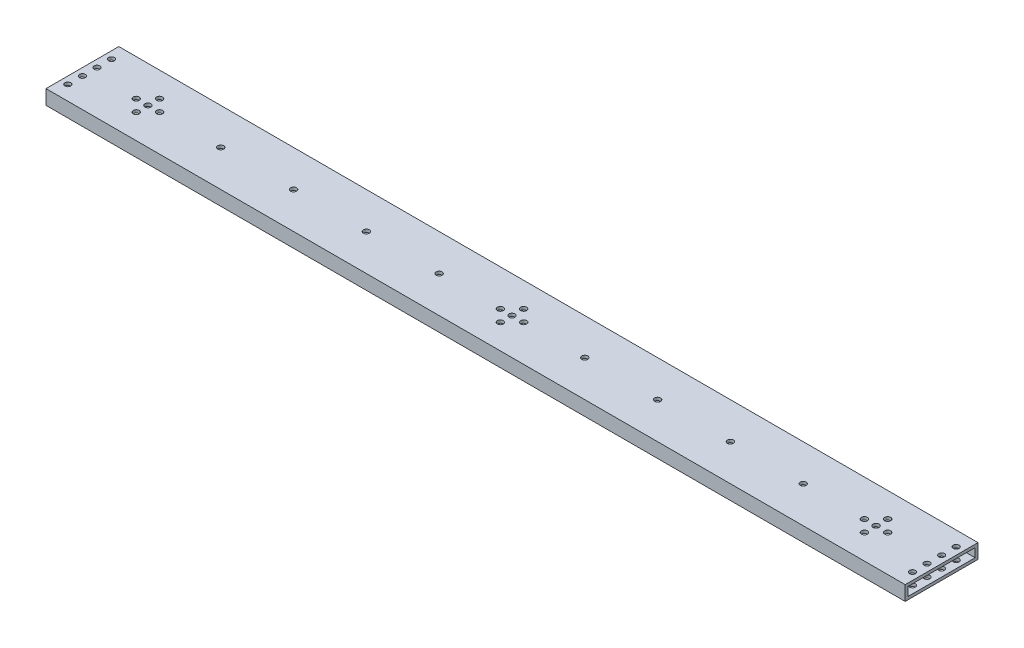
SolidWorks part; units mm, degrees
material "3.0205 (EN-AW 1200)"
ref_plane "前视基准面" through (0, 0, 0) normal (0, 0, 1) x (1, 0, 0)
ref_plane "上视基准面" through (0, 0, 0) normal (0, 1, 0) x (1, 0, 0)
ref_plane "右视基准面" through (0, 0, 0) normal (1, 0, 0) x (0, 0, -1)
sketch "草图1" plane through (0, 0, 0) normal (0, 1, 0) x (1, 0, 0)
  line L1 (-350, 25) -> (350, 25)
  line L2 (-350, 25) -> (-350, -25)
  line L3 (-350, -25) -> (350, -25)
  line L4 (350, 25) -> (350, -25)
  line L5 (-350, 25) -> (350, -25) construction
  line L6 (-350, -25) -> (350, 25) construction
  point P0 (0, 0)
  dimension "D1" = 700
  dimension "D2" = 50
extrude "凸台-拉伸1" add sketch "草图1" along normal blind 10
sketch "草图2" plane through (0, 10, 0) normal (0, 1, 0) x (1, 0, 0)
  line L0 (-350, 0) -> (541.3083, 0) construction
  line L1 (-350, 25) -> (-350, -25) construction
  circle A0 centre (-350, 0) radius 2.05 construction
  circle A15 centre (-300, 0) radius 2.05
  circle A16 centre (-250, 0) radius 2.05
  circle A17 centre (-200, 0) radius 2.05
  circle A18 centre (-150, 0) radius 2.05
  circle A19 centre (-100, 0) radius 2.05
  circle A20 centre (-50, 0) radius 2.05
  circle A21 centre (0, 0) radius 2.05
  circle A22 centre (50, 0) radius 2.05
  circle A23 centre (100, 0) radius 2.05
  circle A24 centre (150, 0) radius 2.05
  circle A25 centre (200, 0) radius 2.05
  circle A26 centre (250, 0) radius 2.05
  circle A28 centre (300, 0) radius 2.05 construction
  circle A29 centre (300, 0) radius 2.05
  circle A30 centre (350, 0) radius 2.05 construction
  circle A33 centre (400, 0) radius 2.05 [skipped]
  circle A34 centre (450, 0) radius 2.05 [skipped]
  dimension "D1" = 4.1
  dimension "D2" = 14
  dimension "D3" = 5
extrude "切除-拉伸2" cut sketch "草图2" against normal through all
sketch "草图3" plane through (0, 10, 0) normal (0, 1, 0) x (1, 0, 0)
  line L0 (-250, 0) -> (-227.6132, 0) construction
  circle A0 centre (-242, 0) radius 2.05
  circle A1 centre (-258, 0) radius 2.05
  circle A2 centre (-8, 0) radius 2.05
  circle A3 centre (8, 0) radius 2.05
  circle A4 centre (242, 0) radius 2.05
  circle A5 centre (258, 0) radius 2.05
  circle A6 centre (-250, 0) radius 2.05 construction
  circle A7 centre (-250, 8) radius 2.05
  circle A8 centre (-250, -8) radius 2.05
  circle A9 centre (0, 8) radius 2.05
  circle A10 centre (0, -8) radius 2.05
  circle A11 centre (250, 8) radius 2.05
  circle A12 centre (250, -8) radius 2.05
  dimension "D1" = 4.1
  dimension "D2" = 4.1
  dimension "D4" = 8
  dimension "D5" = 8
  dimension "D6" = 4.1
  dimension "D7" = 4.1
  dimension "D8" = 8
  dimension "D9" = 8
  dimension "D3" = 3
extrude "切除-拉伸3" cut sketch "草图3" against normal through all
sketch "草图4" plane through (-350, 0, 0) normal (-1, 0, 0) x (0, 0, 1)
  line L0 (0, 0) -> (0, 16.7886) construction
  line L1 (-25, 0) -> (25, 0) construction
  line L2 (25, 5) -> (-32.5838, 5) construction
  line L3 (25, 10) -> (25, 0) construction
  line L4 (-25, 10) -> (25, 10) construction
  line L5 (-23, 8) -> (23, 8)
  line L6 (-23, 8) -> (-23, 2)
  line L7 (-23, 2) -> (23, 2)
  line L8 (23, 8) -> (23, 2)
  line L9 (-23, 8) -> (23, 2) construction
  line L10 (-23, 2) -> (23, 8) construction
  point P8 (0, 5)
  dimension "D1" = 46
  dimension "D2" = 2
extrude "切除-拉伸4" cut sketch "草图4" against normal through all
sketch "草图6" plane through (350, 0, 0) normal (1, 0, 0) x (0, 0, -1)
  line L4 (-25, 0) -> (25, 0)
  line L5 (25, 0) -> (25, 10)
  line L6 (25, 10) -> (-25, 10)
  line L7 (-25, 10) -> (-25, 0)
  line L8 (-25, 0) -> (25, 0)
  line L9 (25, 0) -> (25, 10)
  line L10 (25, 10) -> (-25, 10)
  line L11 (-25, 10) -> (-25, 0)
  dimension "D1" = 0
extrude "切除-拉伸6" cut sketch "草图6" against normal blind 5
mirror "镜向1" about plane through (0, 0, 0) normal (1, 0, 0) of "切除-拉伸6"
sketch "草图7" plane through (0, 10, 0) normal (0, 1, 0) x (1, 0, 0)
  line L0 (340, 32.168) -> (340, -42.8527) construction
  line L1 (345, 25) -> (345, -25) construction
  line L2 (345, 25) -> (-345, 25) construction
  circle A0 centre (340, 15) radius 2
  circle A1 centre (340, 5) radius 2
  circle A2 centre (340, -5) radius 2
  circle A3 centre (340, -15) radius 2
  circle A4 centre (290, 5) radius 2
  circle A5 centre (290, 15) radius 2
  circle A6 centre (290, -5) radius 2
  circle A7 centre (290, -15) radius 2
  dimension "D2" = 4
  dimension "D3" = 10
  dimension "D5" = 2
  dimension "D1" = 5
  dimension "D4" = 3
extrude "切除-拉伸7" cut sketch "草图7" against normal through all
mirror "镜向2" about plane through (0, 0, 0) normal (1, 0, 0) of "切除-拉伸7"
sketch "草图8" plane through (345, 0, 0) normal (1, 0, 0) x (0, 0, -1)
  line L4 (-25, 10) -> (-25, 0)
  line L5 (-25, 0) -> (25, 0)
  line L6 (25, 0) -> (25, 10)
  line L7 (25, 10) -> (-25, 10)
  line L8 (-25, 10) -> (-25, 0)
  line L9 (-25, 0) -> (25, 0)
  line L10 (25, 0) -> (25, 10)
  line L11 (25, 10) -> (-25, 10)
  dimension "D1" = 0
extrude "切除-拉伸8" cut sketch "草图8" against normal blind 50
mirror "镜向3" about plane through (0, 0, 0) normal (1, 0, 0) of "切除-拉伸8"
